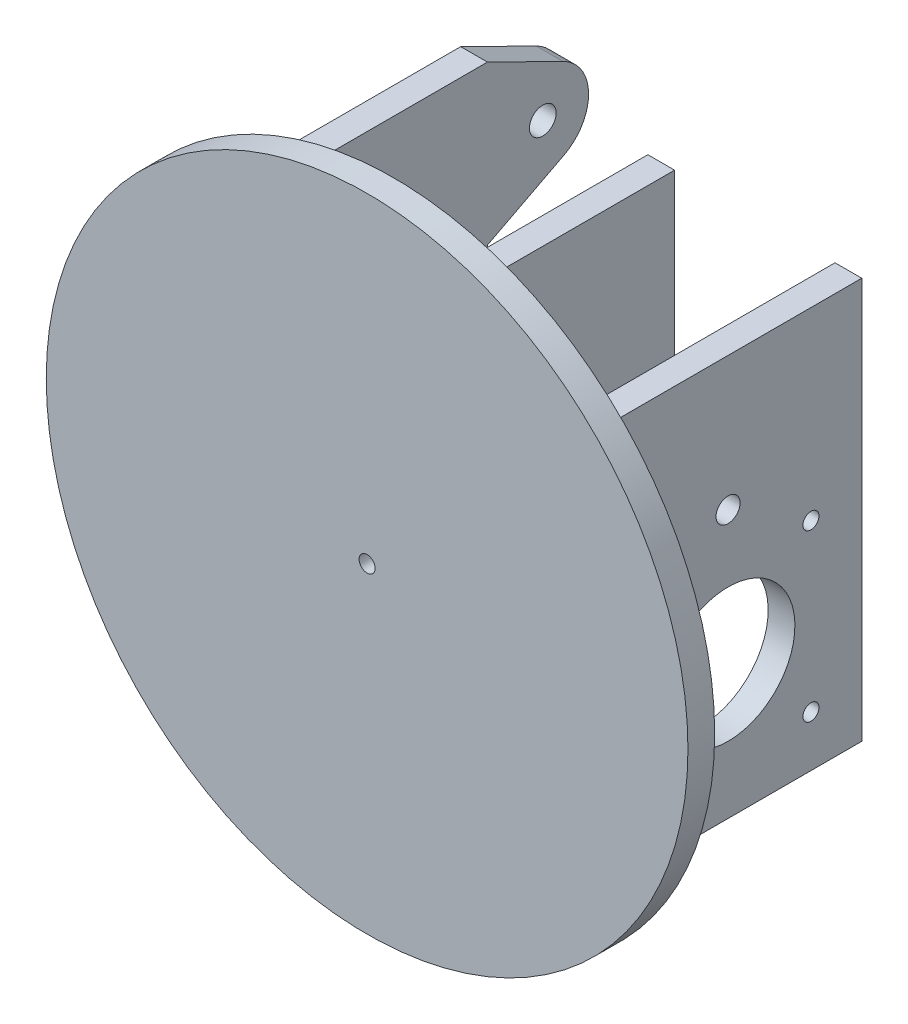
SolidWorks part; units mm, degrees
ref_plane "Front Plane" through (0, 0, 0) normal (0, 0, 1) x (1, 0, 0)
ref_plane "Top Plane" through (0, 0, 0) normal (0, 1, 0) x (1, 0, 0)
ref_plane "Right Plane" through (0, 0, 0) normal (1, 0, 0) x (0, 0, -1)
sketch "Sketch1" plane through (0, 0, 0) normal (0, 0, 1) x (1, 0, 0)
  circle A0 centre (0, 0) radius 60
  circle A1 centre (0, 0) radius 1.5
  dimension "D1" = 120
  dimension "D2" = 3
extrude "Boss-Extrude1" add sketch "Sketch1" along normal blind 5
sketch "Sketch2" plane through (0, 0, 0) normal (0, 0, -1) x (-1, 0, 0)
  line L0 (37.5, 37.5) -> (-37.5, -37.5) construction
  line L1 (-37.5, 37.5) -> (37.5, -37.5) construction
  line L3 (-37.5, 37.5) -> (-32.5, 37.5)
  line L4 (-37.5, 37.5) -> (-37.5, -37.5)
  line L5 (-37.5, -37.5) -> (-32.5, -37.5)
  line L6 (-32.5, 37.5) -> (-32.5, -37.5)
  line L7 (37.5, 37.5) -> (32.5, 37.5)
  line L8 (37.5, 37.5) -> (37.5, -37.5)
  line L9 (37.5, -37.5) -> (32.5, -37.5)
  line L10 (32.5, 37.5) -> (32.5, -37.5)
  line L11 (-2.5, -37.5) -> (2.5, -37.5)
  line L12 (-2.5, -37.5) -> (-2.5, 37.5)
  line L13 (-2.5, 37.5) -> (2.5, 37.5)
  line L14 (2.5, -37.5) -> (2.5, 37.5)
  line L15 (-2.5, -37.5) -> (2.5, 37.5) construction
  line L16 (-2.5, 37.5) -> (2.5, -37.5) construction
  point P7 (0, 0)
  dimension "D1" = 75
  dimension "D2" = 5
extrude "Boss-Extrude2" add sketch "Sketch2" along normal blind 50
sketch "Sketch3" plane through (32.5, 0, 0) normal (-1, 0, 0) x (0, 0, 1)
  line L0 (-50, -37.5) -> (0, 12.5) construction
  line L1 (-50, -37.5) -> (-50, 37.5) construction
  line L2 (-50, -37.5) -> (0, -37.5) construction
  line L3 (0, -37.5) -> (0, 37.5) construction
  line L4 (0, -37.5) -> (-50, 12.5) construction
  circle A0 centre (-40.5, 3) radius 1.5
  circle A1 centre (-9.5, 3) radius 1.5
  circle A2 centre (-9.5, -28) radius 1.5
  circle A3 centre (-40.5, -28) radius 1.5
  circle A4 centre (-25, -12.5) radius 12.5
  dimension "D2" = 3
  dimension "D4" = 25
  dimension "D1" = 45
  dimension "D3" = 31
extrude "Cut-Extrude1" cut sketch "Sketch3" against normal through all
sketch "Sketch5" plane through (-2.5, 0, 0) normal (-1, 0, 0) x (0, 0, 1)
  line L0 (-25, -37.5) -> (-25, 37.5) construction
  line L1 (-50, -37.5) -> (0, -37.5) construction
  line L2 (-50, 37.5) -> (0, 37.5) construction
  line L4 (-23.4125, -14.0875) -> (-26.5875, -14.0875)
  line L5 (-23.4125, -14.0875) -> (-23.4125, -10.9125)
  line L6 (-23.4125, -10.9125) -> (-26.5875, -10.9125)
  line L7 (-26.5875, -14.0875) -> (-26.5875, -10.9125)
  line L8 (-23.4125, -14.0875) -> (-26.5875, -10.9125) construction
  line L9 (-23.4125, -10.9125) -> (-26.5875, -14.0875) construction
  circle A0 centre (-25, -12.5) radius 2.2451
  circle A1 centre (-25, 12.5) radius 2.2451
  dimension "D3" = 3.175
  dimension "D1" = 25
  dimension "D2" = 25
extrude "Cut-Extrude4" cut sketch "Sketch5" against normal blind 53 and the other way through all contours A1
sketch "Sketch6" plane through (-37.5, 0, 0) normal (-1, 0, 0) x (0, 0, 1)
  line L0 (-50, -37.5) -> (0, 12.5) construction
  line L1 (0, -37.5) -> (-50, 12.5) construction
  circle A0 centre (-40.5, 3) radius 1.5
  circle A1 centre (-9.5, 3) radius 1.5
  circle A2 centre (-9.5, -28) radius 1.5
  circle A3 centre (-40.5, -28) radius 1.5
  circle A4 centre (-25, -12.5) radius 12.5
  dimension "D1" = 3
  dimension "D3" = 25
  dimension "D2" = 31
extrude "Cut-Extrude5" cut sketch "Sketch6" against normal up to surface (5 mm away) up to face at (-32.5, 10.2549, -25)
sketch "Sketch7" plane through (-37.5, 0, 0) normal (-1, 0, 0) x (0, 0, 1)
  line L0 (-25, -12.5) -> (-60.3553, 22.8553) construction
  line L1 (0, 60) -> (0, -60) construction
  line L2 (-50, 37.5) -> (-64.1385, 30.5347)
  line L3 (-64.2907, 15.2528) -> (-50, 7.8553)
  line L4 (-50, -37.5) -> (-50, 37.5) construction
  line L6 (-50, 7.8553) -> (-50, 37.5)
  circle A2 centre (-25, -12.5) radius 12.5 construction
  circle A3 centre (-60.3553, 22.8553) radius 2.5
  arc A4 (-64.2907, 15.2528) -> (-64.1385, 30.5347) centre (-60.3553, 22.8553) cw
  dimension "D3" = 5
  dimension "D1" = 50
  dimension "D2" = 45
  dimension "D4" = 15
extrude "Boss-Extrude4" add sketch "Sketch7" against normal blind 5
